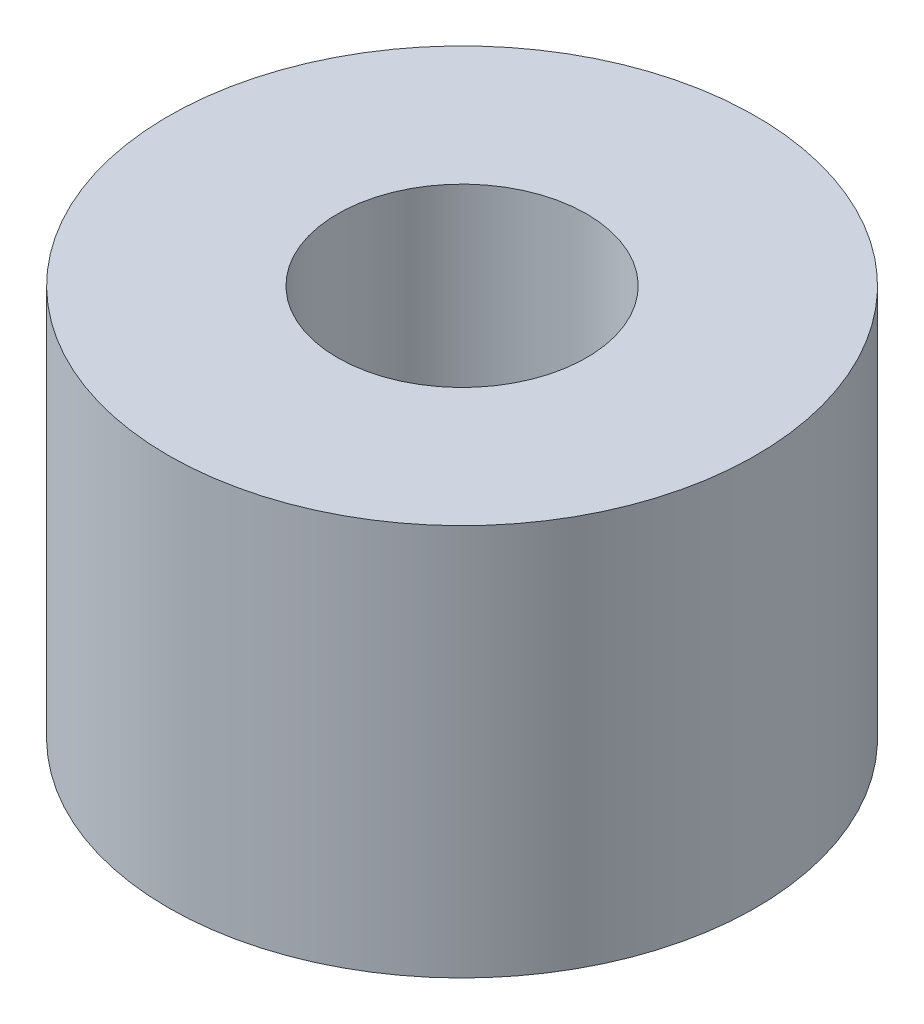
SolidWorks part; units mm, degrees
ref_plane "Front Plane" through (0, 0, 0) normal (0, 0, 1) x (1, 0, 0)
ref_plane "Top Plane" through (0, 0, 0) normal (0, 1, 0) x (1, 0, 0)
ref_plane "Right Plane" through (0, 0, 0) normal (1, 0, 0) x (0, 0, -1)
sketch "Sketch1" plane through (0, 0, 0) normal (0, 1, 0) x (1, 0, 0)
  circle A0 centre (0, 0) radius 4.7625
  circle A1 centre (0, 0) radius 0.635
  dimension "D1" = 9.525
  dimension "D2" = 1.27
extrude "Boss-Extrude1" add sketch "Sketch1" along normal blind 6.35
hole_wizard "#10-32 Tapped Hole1" positions "Sketch3" profile "Sketch2" tap size "#10-32" standard "ANSI Inch" end condition through all
sketch "Sketch3" plane through (0, 6.35, 0) normal (0, 1, 0) x (1, 0, 0)
  point P0 (0, 0)
sketch "Sketch2" plane through (0, 6.35, 0) normal (1, 0, 0) x (0, 0, 1)
  line L0 (0, 0) -> (0, 6.35)
  line L1 (0, 6.35) -> (2.0193, 6.35)
  line L2 (2.0193, 6.35) -> (2.0193, 0)
  line L5 (2.0193, 0) -> (0, 0)
  line L11 (0, -6.35) -> (0, 107.95) construction
  dimension "Thread Major Dia." = 4.0386
  dimension "Thru Tap Drill Depth" = 6.35
